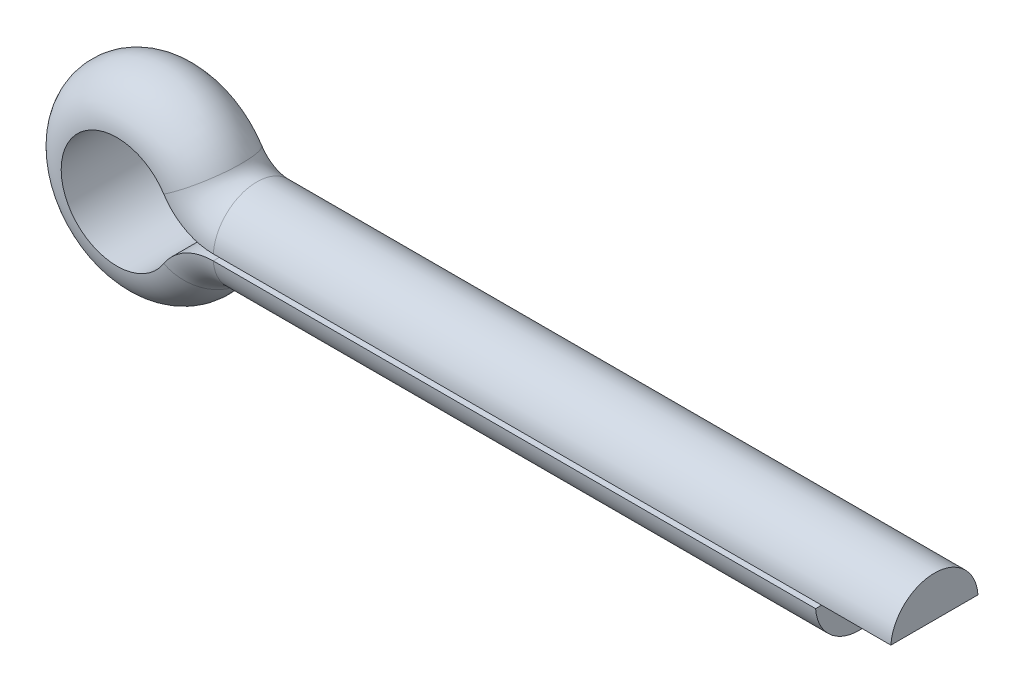
SolidWorks part; units mm, degrees
ref_plane "Спереди" through (0, 0, 0) normal (0, 0, 1) x (1, 0, 0)
ref_plane "Сверху" through (0, 0, 0) normal (0, 1, 0) x (1, 0, 0)
ref_plane "Справа" through (0, 0, 0) normal (1, 0, 0) x (0, 0, -1)
sketch "Эскиз1" plane through (0, 0, 0) normal (1, 0, 0) x (0, 0, -1)
  line L0 (-1.4465, 0.1) -> (1.4465, 0.1)
  line L1 (-1.8623, 0) -> (2.0338, 0) construction
  arc A0 (-1.4465, 0.1) -> (1.4465, 0.1) centre (0, 0) cw
  dimension "D1" = 2.9
  dimension "D2" = 0.2
sketch "Эскиз2" plane through (0, 0, 0) normal (0, 0, 1) x (1, 0, 0)
  line L0 (0, 1.45) -> (-22.5, 1.45)
  line L1 (0, 0.1) -> (0, 1.45) construction
  line L2 (-22.5, -1.45) -> (-2.5, -1.45)
  line L3 (1.6678, 0) -> (-30.578, 0) construction
  arc A0 (-22.5, 1.45) -> (-23.0058, 1.7266) centre (-22.5, 2.0507) cw
  arc A1 (-23.0058, 1.7266) -> (-23.0058, -1.7266) centre (-25.7, 0) ccw
  arc A2 (-23.0058, -1.7266) -> (-22.5, -1.45) centre (-22.5, -2.0507) cw
  dimension "D1" = 6.4
  dimension "D4" = 6.4
  dimension "D2" = 2.5
  dimension "D3" = 20
sweep "По траектории1" add profiles "Эскиз1" path "Эскиз2"
